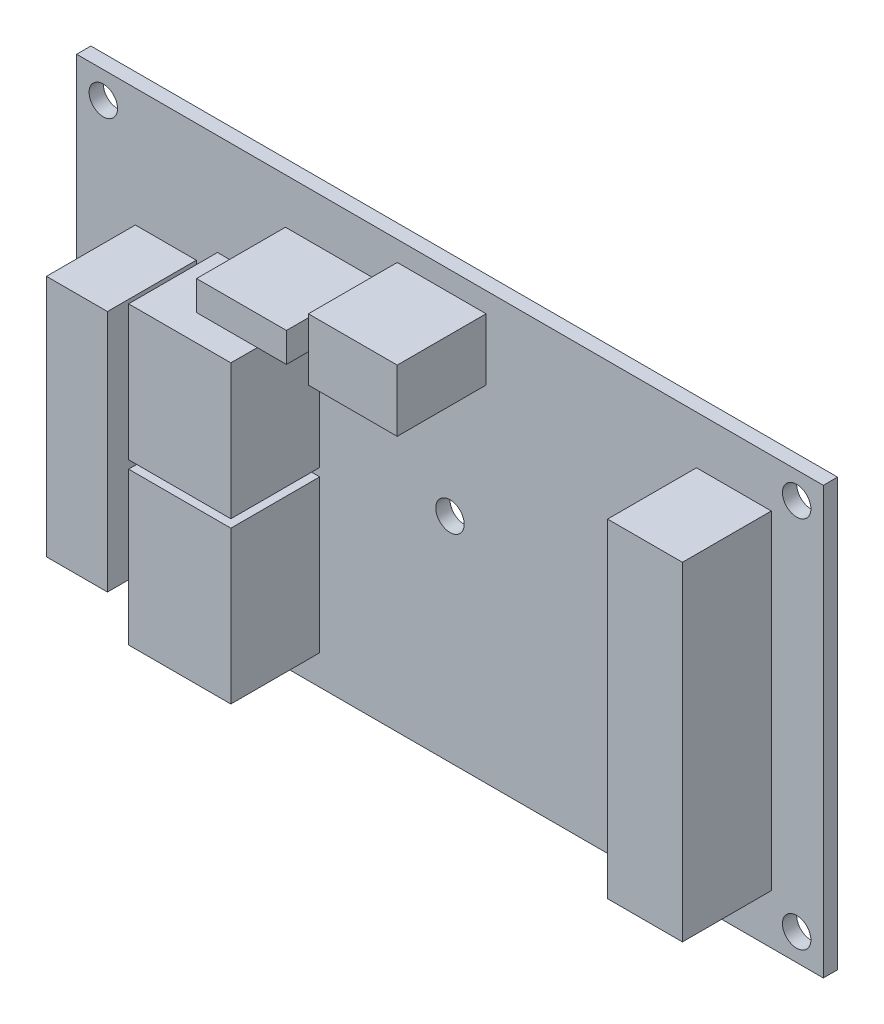
SolidWorks part; units mm, degrees
ref_plane "Top Plane" through (0, 0, 0) normal (0, 0, 1) x (1, 0, 0)
ref_plane "Right Plane" through (0, 0, 0) normal (0, 1, 0) x (1, 0, 0)
ref_plane "Front Plane" through (0, 0, 0) normal (1, 0, 0) x (0, 0, -1)
sketch "Sketch1" plane through (0, 0, 0) normal (0, 0, 1) x (1, 0, 0)
  line L0 (-42, 24) -> (42, -24) construction
  line L1 (-42, 24) -> (42, 24)
  line L2 (-42, 24) -> (-42, -24)
  line L3 (-42, -24) -> (42, -24)
  line L4 (42, 24) -> (42, -24)
  dimension "D1" = 84
  dimension "D2" = 48
extrude "Boss-Extrude1" add sketch "Sketch1" along normal mid plane 1.6
sketch "Sketch2" plane through (0, 0, 0.8) normal (0, 0, 1) x (1, 0, 0)
  line L1 (-42, -24) -> (42, -24) construction
  line L3 (-42, 24) -> (-42, -24) construction
  circle A0 centre (-39, -21) radius 1.6
  circle A1 centre (-39, 21) radius 1.6
  circle A2 centre (0, 0) radius 1.6
  circle A3 centre (39, -21) radius 1.6
  circle A4 centre (39, 21) radius 1.6
  point P12 (0, 0)
  point P15 (0, 0)
  point P16 (0, 0)
  point P17 (0, 0)
  point P18 (0, 0)
  point P19 (0, 0)
  dimension "D1" = 3.2
  dimension "D2" = 3
  dimension "D3" = 3
  dimension "D4" = 42
  dimension "D5" = 78
extrude "Cut-Extrude1" cut sketch "Sketch2" against normal through all
sketch "Sketch3" plane through (0, 0, 0.8) normal (0, 0, 1) x (1, 0, 0)
  line L1 (-35.3973, -16.6682) -> (-28.5351, -16.6682)
  line L2 (-35.3973, -16.6682) -> (-35.3973, 10.6639)
  line L3 (-35.3973, 10.6639) -> (-28.5351, 10.6639)
  line L4 (-28.5351, -16.6682) -> (-28.5351, 10.6639)
  line L5 (-18.5117, 15.5761) -> (-8.401, 15.5761)
  line L6 (-18.5117, 15.5761) -> (-18.5117, 18.8889)
  line L7 (-18.5117, 18.8889) -> (-8.401, 18.8889)
  line L8 (-8.401, 15.5761) -> (-8.401, 18.8889)
  line L9 (-5.9323, 14.8015) -> (4.0634, 14.8015)
  line L10 (-5.9323, 14.8015) -> (-5.9323, 21.7448)
  line L11 (-5.9323, 21.7448) -> (4.0634, 21.7448)
  line L12 (4.0634, 14.8015) -> (4.0634, 21.7448)
  line L13 (-26.1552, -20.6367) -> (-14.6523, -20.6367)
  line L14 (-26.1552, -20.6367) -> (-26.1552, -3.5013)
  line L15 (-26.1552, -3.5013) -> (-14.6523, -3.5013)
  line L16 (-14.6523, -20.6367) -> (-14.6523, -3.5013)
  line L17 (-26.1552, -2.5874) -> (-14.6523, -2.5874)
  line L18 (-26.1552, -2.5874) -> (-26.1552, 12.6059)
  line L19 (-26.1552, 12.6059) -> (-14.6523, 12.6059)
  line L20 (-14.6523, -2.5874) -> (-14.6523, 12.6059)
  line L21 (-12.193, -20.8652) -> (4.2284, -20.8652) construction
  line L22 (-12.193, -20.8652) -> (-12.193, 12.7202) construction
  line L23 (-12.193, 12.7202) -> (4.2284, 12.7202) construction
  line L24 (4.2284, -20.8652) -> (4.2284, 12.7202) construction
  line L25 (6.7924, -20.8652) -> (25.7555, -20.8652) construction
  line L26 (6.7924, -20.8652) -> (6.7924, 21.8591) construction
  line L27 (6.7924, 21.8591) -> (25.7555, 21.8591) construction
  line L28 (25.7555, -20.8652) -> (25.7555, 21.8591) construction
  line L29 (27.7283, -18.4133) -> (36.1489, -18.4133)
  line L30 (27.7283, -18.4133) -> (27.7283, 18.5743)
  line L31 (27.7283, 18.5743) -> (36.1489, 18.5743)
  line L32 (36.1489, -18.4133) -> (36.1489, 18.5743)
  point P24 (0, 0)
  point P25 (27.7283, -18.4133)
  point P34 (36.9359, 19.3613)
  point P35 (36.1489, 18.5743)
extrude "Boss-Extrude2" add sketch "Sketch3" along normal blind 10
sketch "Sketch4" plane through (0, 0, 0.8) normal (0, 0, 1) x (1, 0, 0)
  line L0 (-3.9823, -20.8652) -> (-3.9823, 12.7202) construction
  line L1 (-12.193, -20.8652) -> (4.2284, -20.8652) construction
  line L2 (-12.193, 12.7202) -> (4.2284, 12.7202) construction
  line L3 (-12.193, -4.0725) -> (4.2284, -4.0725) construction
  line L4 (-12.193, -20.8652) -> (-12.193, 12.7202) construction
  line L5 (4.2284, -20.8652) -> (4.2284, 12.7202) construction
  line L6 (16.2739, -20.8652) -> (16.2739, 21.8591) construction
  line L7 (6.7924, -20.8652) -> (25.7555, -20.8652) construction
  line L8 (6.7924, 21.8591) -> (25.7555, 21.8591) construction
  line L9 (6.7924, 0.4969) -> (25.7555, 0.4969) construction
  line L10 (6.7924, -20.8652) -> (6.7924, 21.8591) construction
  line L11 (25.7555, -20.8652) -> (25.7555, 21.8591) construction
